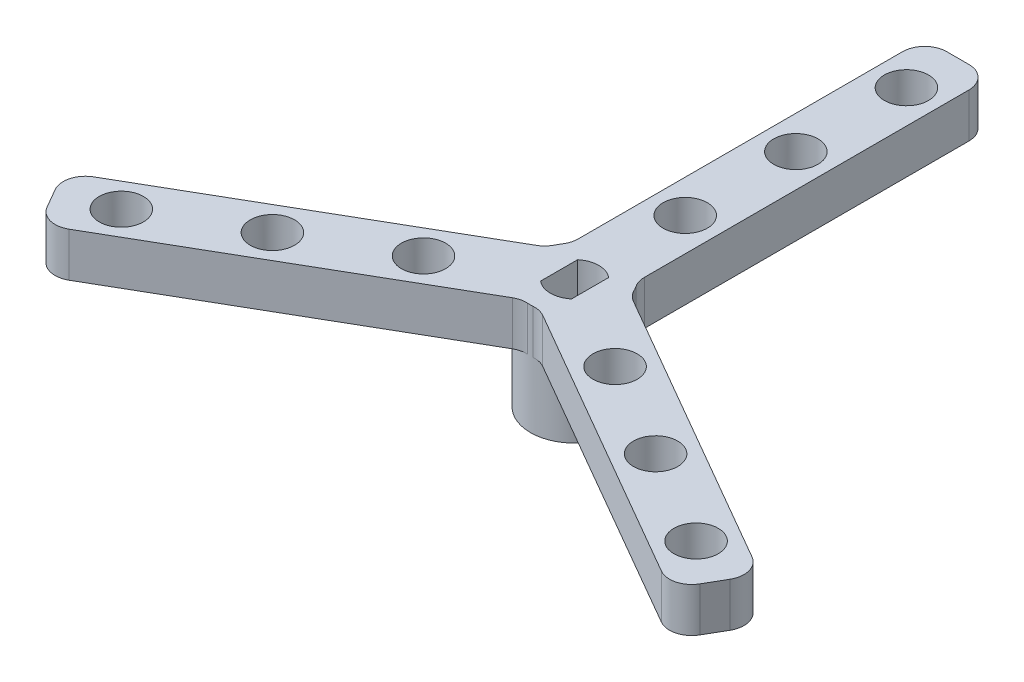
SolidWorks part; units mm, degrees
ref_plane "Front Plane" through (0, 0, 0) normal (0, 0, 1) x (1, 0, 0)
ref_plane "Top Plane" through (0, 0, 0) normal (0, 1, 0) x (1, 0, 0)
ref_plane "Right Plane" through (0, 0, 0) normal (1, 0, 0) x (0, 0, -1)
sketch "Sketch1" plane through (0, 0, 0) normal (0, 1, 0) x (1, 0, 0)
  line L0 (1.7875, 5.8114) -> (1.7875, 1.6201)
  line L2 (-1.3625, 5.6407) -> (-1.3625, 1.7907)
  line L4 (1.4375, 5.6407) -> (1.4375, 1.7907)
  line L5 (-1.7125, 5.8114) -> (-1.7125, 1.6201)
  arc A1 (-1.3625, 5.6407) -> (1.4375, 5.6407) centre (0.0375, 3.7161) cw
  arc A2 (-1.3625, 1.7907) -> (1.4375, 1.7907) centre (0.0375, 3.7154) ccw
  arc A3 (-1.7125, 5.8114) -> (1.7875, 5.8114) centre (0.0375, 3.7161) cw
  arc A4 (-1.7125, 1.6201) -> (1.7875, 1.6201) centre (0.0375, 3.7154) ccw
  circle A5 centre (0.0375, 3.7154) radius 5
  dimension "D1" = 3.85
  dimension "D3" = 2.38
  dimension "D4" = 2.38
  dimension "D6" = 10
  dimension "D2" = 2.8
  dimension "D5" = 0.35
extrude "Boss-Extrude1" add sketch "Sketch1" along normal blind 12.5 contours A5 A4 L5 A3 L0
sketch "Sketch2" plane through (0, 12.5, 0) normal (0, 1, 0) x (1, 0, 0)
  line L0 (0.0375, 47.0226) -> (0.0375, 7.0226) construction
  line L1 (0.0375, 8.7154) -> (0.0375, 9.9323) construction
  line L2 (4.7766, 5.3094) -> (1.0266, -1.1858)
  line L3 (-3.7125, 7.0226) -> (3.7875, 7.0226)
  line L4 (-3.7125, 7.0226) -> (-3.7125, 47.0226)
  line L5 (3.7875, 7.0226) -> (3.7875, 47.0226)
  line L6 (-3.7125, 47.0226) -> (3.7875, 47.0226)
  line L7 (4.7766, 5.3094) -> (39.4176, -14.6906)
  line L8 (1.0266, -1.1858) -> (35.6676, -21.1858)
  line L9 (39.4176, -14.6906) -> (35.6676, -21.1858)
  line L10 (37.5426, -17.9382) -> (2.9016, 2.0618) construction
  line L11 (-4.7016, 5.3094) -> (-0.9516, -1.1858)
  line L12 (-4.7016, 5.3094) -> (-39.3427, -14.6906)
  line L13 (-0.9516, -1.1858) -> (-35.5927, -21.1858)
  line L14 (-39.3427, -14.6906) -> (-35.5927, -21.1858)
  line L15 (-2.8266, 2.0618) -> (-37.4677, -17.9382) construction
  circle A0 centre (0.0375, 3.7154) radius 5 construction
  point P6 (0.0375, 3.7154)
  dimension "D1" = 7.5
  dimension "D2" = 40
  dimension "D3" = 0
  dimension "D4" = 7.5
  dimension "D5" = 40
  dimension "D6" = 120
  dimension "D7" = 7.5
  dimension "D8" = 40
  dimension "D9" = 120
extrude "Boss-Extrude4" add sketch "Sketch2" against normal blind 5
sketch "Sketch4" plane through (0, 12.5, 0) normal (0, 1, 0) x (1, 0, 0)
  line L0 (3.7875, 7.0226) -> (3.7875, 47.0226) construction
  line L1 (0.0375, 3.7161) -> (37.5426, -17.9382) construction
  line L2 (35.6676, -21.1858) -> (39.4176, -14.6906) construction
  line L3 (0.0375, 3.7161) -> (-37.4677, -17.9382) construction
  line L4 (-39.3427, -14.6906) -> (-35.5927, -21.1858) construction
  circle A0 centre (0.0375, 16.2161) radius 2.5
  circle A1 centre (0.0375, 28.7161) radius 2.5
  circle A2 centre (0.0375, 41.2161) radius 2.5
  circle A3 centre (-10.788, -2.5337) radius 2.5
  circle A4 centre (-21.6135, -8.7834) radius 2.5
  circle A5 centre (-32.439, -15.0331) radius 2.5
  circle A6 centre (10.8629, -2.5337) radius 2.5
  circle A7 centre (21.6884, -8.7834) radius 2.5
  circle A8 centre (32.5139, -15.0331) radius 2.5
  point P5 (0.0375, 3.7161)
  dimension "D1" = 5
  dimension "D2" = 5
  dimension "D7" = 5
  dimension "D3" = 12.5
  dimension "D4" = 12.5
  dimension "D5" = 3.75
  dimension "D6" = 3.75
  dimension "D8" = 3.75
  dimension "D9" = 12.5
extrude "Cut-Extrude1" cut sketch "Sketch4" against normal blind 100
fillet "Fillet1" radius 2.5 6 edges at (4.7766, 10, -5.3094) (3.7875, 10, -7.0226) (-3.7125, 10, -7.0226) (-4.7016, 10, -5.3094) (-0.9516, 10, 1.1858) (1.0266, 10, 1.1858)
fillet "Fillet2" radius 2.5 6 edges at (-3.7125, 10, -47.0226) (3.7875, 10, -47.0226) (39.4176, 10, 14.6906) (35.6676, 10, 21.1858) (-39.3427, 10, 14.6906) (-35.5927, 10, 21.1858)
